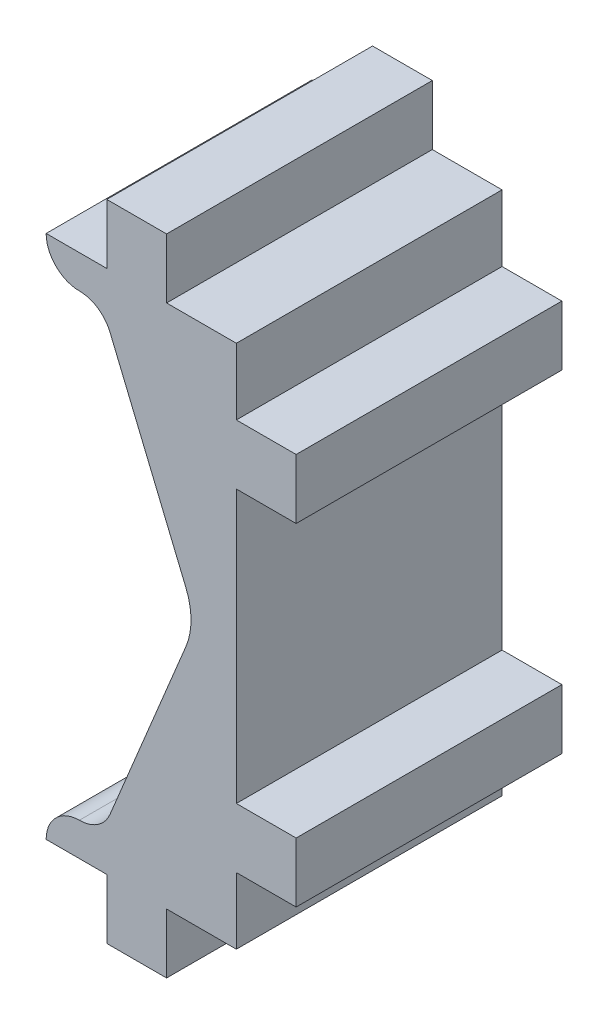
SolidWorks part; units mm, degrees
ref_plane "Přední rovina" through (0, 0, 0) normal (0, 0, 1) x (1, 0, 0)
ref_plane "Horní rovina" through (0, 0, 0) normal (0, 1, 0) x (1, 0, 0)
ref_plane "Pravá rovina" through (0, 0, 0) normal (1, 0, 0) x (0, 0, -1)
sketch "Skica1" plane through (0, 0, 0) normal (0, 0, 1) x (1, 0, 0)
  line L1 (-4.5263, 7.9) -> (1.2, 7.9) construction
  line L2 (1.2, 7.9) -> (1.2, 5.9)
  line L3 (1.2, 5.9) -> (3, 5.9)
  line L4 (3, 5.9) -> (3, 4.1)
  line L5 (3, 4.1) -> (1.2, 4.1)
  line L6 (1.2, 4.1) -> (1.2, -4.1)
  line L7 (-1000, 0) -> (49000, 0) construction
  line L8 (3, -4.1) -> (1.2, -4.1)
  line L9 (3, -5.9) -> (3, -4.1)
  line L10 (1.2, -5.9) -> (3, -5.9)
  line L11 (1.2, -7.9) -> (1.2, -5.9)
  line L14 (0, 0) -> (-2.6024, 6.2827)
  line L15 (-4.5263, -7.9) -> (1.2, -7.9) construction
  line L16 (0, 0) -> (-2.6024, -6.2827)
  line L17 (1.2, 7.9) -> (-0.9, 7.9)
  line L18 (-0.9, 7.9) -> (-0.9, 9.7)
  line L19 (-0.9, 9.7) -> (-2.7, 9.7)
  line L20 (-2.7, 9.7) -> (-2.7, 7.9)
  line L21 (-2.7, 7.9) -> (-4.5263, 7.9)
  line L22 (-2.7, -9.7) -> (-2.7, -7.9)
  line L23 (-0.9, -9.7) -> (-2.7, -9.7)
  line L24 (-0.9, -7.9) -> (-0.9, -9.7)
  line L25 (1.2, -7.9) -> (-0.9, -7.9)
  line L26 (-2.7, -7.9) -> (-4.5263, -7.9)
  arc A0 (-2.6024, 6.2827) -> (-3.5263, 6.9) centre (-3.5263, 5.9) ccw
  arc A1 (-3.5263, 6.9) -> (-4.5263, 7.9) centre (-3.5263, 7.9) cw
  arc A2 (-2.6024, -6.2827) -> (-3.5263, -6.9) centre (-3.5263, -5.9) cw
  arc A3 (-3.5263, -6.9) -> (-4.5263, -7.9) centre (-3.5263, -7.9) ccw
  point P14 (1.2, 0)
  dimension "D7" = 1
  dimension "D8" = 1
  dimension "D1" = 67.5
  dimension "D2" = 8.2
  dimension "D3" = 1.2
  dimension "D4" = 1.8
  dimension "D5" = 1.8
  dimension "D6" = 15.8
  dimension "D9" = 2.1
extrude "Přidat vysunutím1" add sketch "Skica1" along normal blind 8
fillet "Zaoblit1" radius 2 1 edges at (0, 0, 4)
